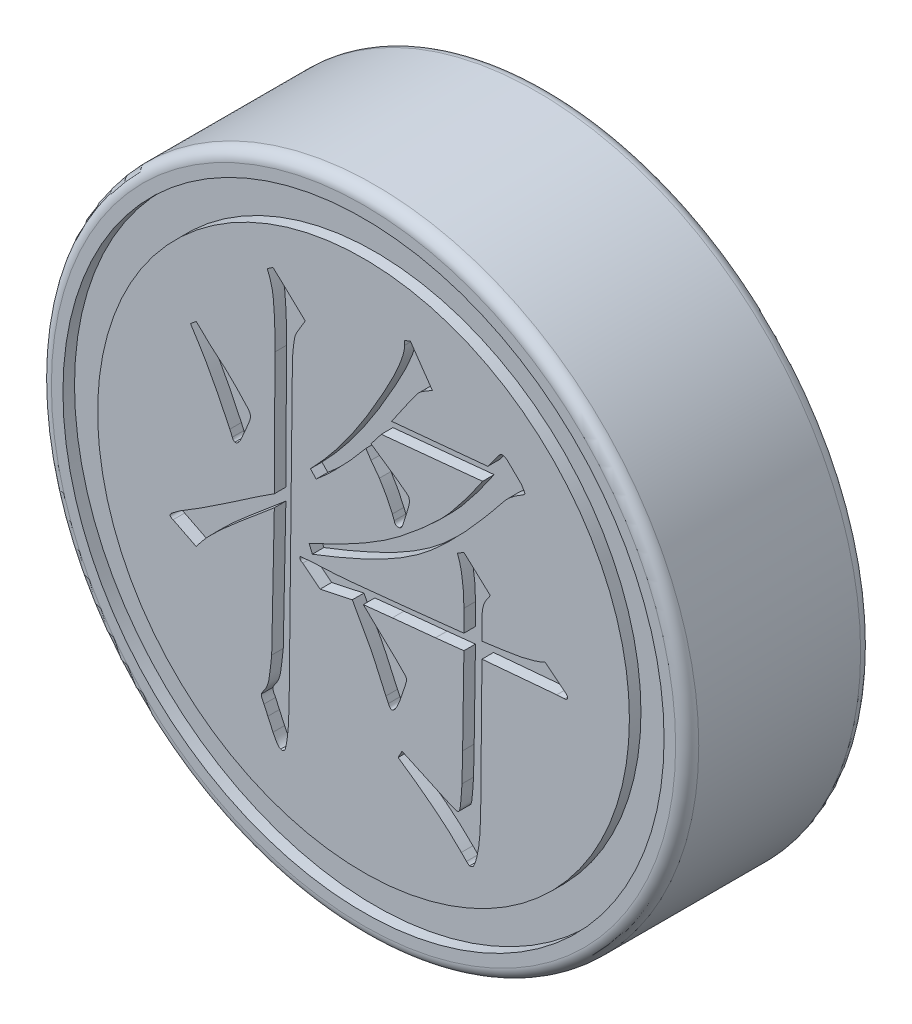
SolidWorks part; units mm, degrees
ref_plane "前视基准面" through (0, 0, 0) normal (0, 0, 1) x (1, 0, 0)
ref_plane "上视基准面" through (0, 0, 0) normal (0, 1, 0) x (1, 0, 0)
ref_plane "右视基准面" through (0, 0, 0) normal (1, 0, 0) x (0, 0, -1)
sketch "草图1" plane through (0, 0, 0) normal (0, 0, 1) x (1, 0, 0)
  circle A0 centre (0, 0) radius 14
extrude "凸台-拉伸1" add sketch "草图1" along normal blind 8
sketch "草图2" plane through (0, 0, 8) normal (0, 0, 1) x (1, 0, 0)
  circle A0 centre (0, 0) radius 13
  circle A1 centre (0, 0) radius 11.5
extrude "切除-拉伸1" cut sketch "草图2" against normal blind 0.5
sketch "草图3" plane through (0, 0, 0) normal (0, 0, -1) x (-1, 0, 0)
  circle A0 centre (0, 0) radius 5.1
extrude "切除-拉伸2" cut sketch "草图3" against normal blind 5
chamfer "倒角1" distance 0.5 angle 45 1 edges at (-5.1, 0, 0)
fillet "圆角1" radius 0.5 2 edges at (14, 0, 8) (14, 0, 0)
sketch "草图5" plane through (0, 0, 8) normal (0, 0, 1) x (1, 0, 0)
  text T0 "将" font "汉仪长仿宋体" height 13
extrude "切除-拉伸4" cut sketch "草图5" against normal blind 0.5
